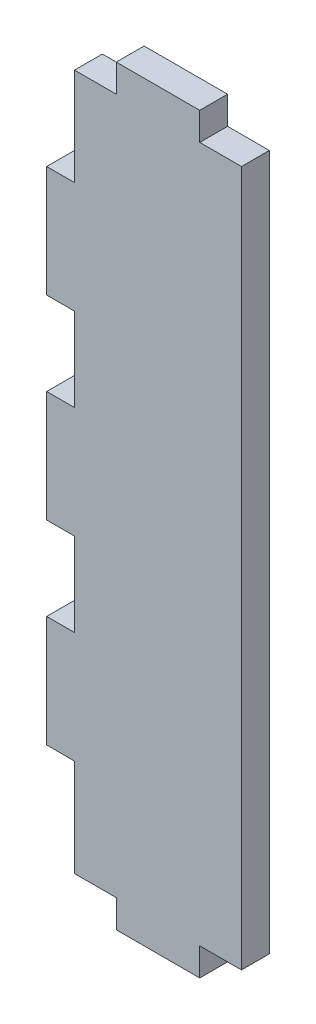
SolidWorks part; units mm, degrees
ref_plane "Front Plane" through (0, 0, 0) normal (0, 0, 1) x (1, 0, 0)
ref_plane "Top Plane" through (0, 0, 0) normal (0, 1, 0) x (1, 0, 0)
ref_plane "Right Plane" through (0, 0, 0) normal (1, 0, 0) x (0, 0, -1)
sketch "Sketch1" plane through (0, 0, 0) normal (0, 0, 1) x (1, 0, 0)
  line L0 (47.5, 165) -> (55, 165)
  line L1 (25, 165) -> (32.5, 165)
  line L2 (25, 165) -> (25, 147.5)
  line L3 (25, 40) -> (32.5, 40)
  line L4 (55, 165) -> (55, 40)
  line L6 (47.5, 165) -> (47.5, 170)
  line L7 (47.5, 170) -> (32.5, 170)
  line L8 (32.5, 165) -> (32.5, 170)
  line L9 (40, 165) -> (32.5, 170) construction
  line L10 (47.5, 170) -> (40, 165) construction
  line L11 (55, 102.5) -> (47.5, 102.5) construction
  line L12 (47.5, 35) -> (40, 40) construction
  line L13 (40, 40) -> (32.5, 35) construction
  line L14 (32.5, 40) -> (32.5, 35)
  line L15 (47.5, 35) -> (32.5, 35)
  line L16 (47.5, 40) -> (47.5, 35)
  line L17 (47.5, 40) -> (55, 40)
  line L18 (25, 92.5) -> (25, 77.5)
  line L19 (25, 112.5) -> (20, 112.5)
  line L21 (25, 92.5) -> (20, 92.5)
  line L22 (20, 112.5) -> (20, 92.5)
  line L23 (25, 102.5) -> (20, 92.5) construction
  line L24 (25, 102.5) -> (20, 112.5) construction
  line L25 (25, 77.5) -> (20, 77.5)
  line L26 (20, 77.5) -> (20, 57.5)
  line L27 (25, 57.5) -> (20, 57.5)
  line L28 (25, 112.5) -> (20, 112.5)
  line L29 (20, 112.5) -> (20, 92.5)
  line L30 (25, 92.5) -> (20, 92.5)
  line L31 (25, 147.5) -> (20, 147.5)
  line L32 (20, 147.5) -> (20, 127.5)
  line L33 (25, 127.5) -> (20, 127.5)
  line L34 (25, 57.5) -> (25, 40)
  line L35 (25, 127.5) -> (25, 112.5)
  point P5 (40, 165)
  point P17 (40, 40)
  point P18 (25, 102.5)
  dimension "D1" = 30
  dimension "D2" = 5
  dimension "D3" = 15
  dimension "D4" = 5
  dimension "D5" = 20
  dimension "D6" = 2
  dimension "D7" = 2
extrude "Boss-Extrude1" add sketch "Sketch1" against normal blind 5 contours L33 L35 L19 L22 L21 L18 L25 L26 L27 L34 L3 L14 L15 L16 L17 L4 L0 L6 L7 L8 L1 L2 L31 L32
